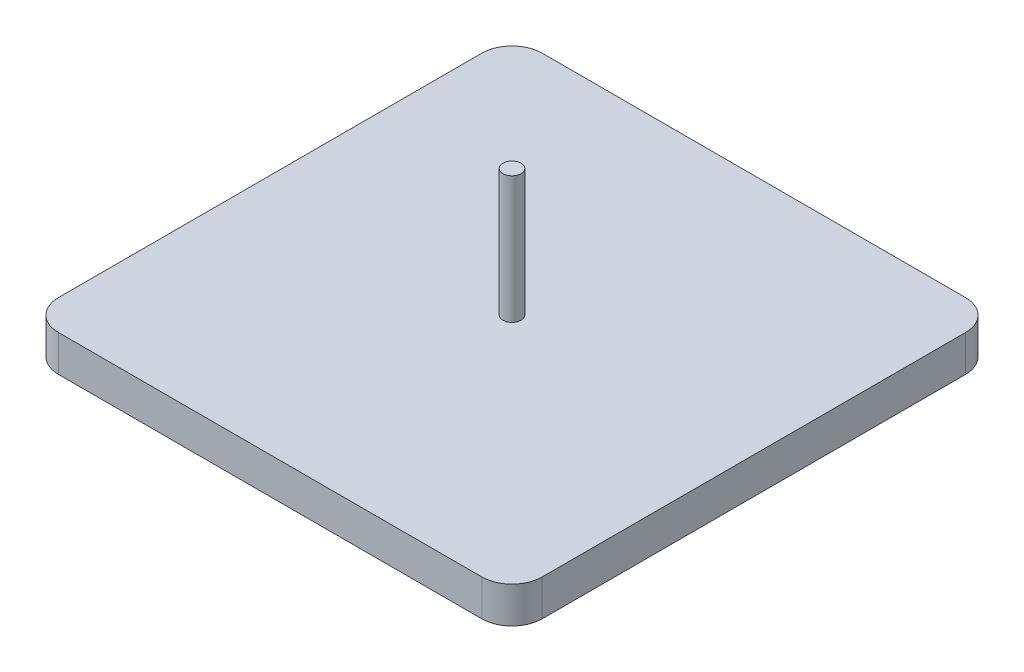
SolidWorks part; units mm, degrees
ref_plane "Front Plane" through (0, 0, 0) normal (0, 0, 1) x (1, 0, 0)
ref_plane "Top Plane" through (0, 0, 0) normal (0, 1, 0) x (1, 0, 0)
ref_plane "Right Plane" through (0, 0, 0) normal (1, 0, 0) x (0, 0, -1)
sketch "Sketch1" plane through (0, 0, 0) normal (0, 1, 0) x (1, 0, 0)
  line L1 (-21.4242, 53.9849) -> (58.5758, 53.9849)
  line L2 (-21.4242, 53.9849) -> (-21.4242, -26.0151)
  line L3 (-21.4242, -26.0151) -> (58.5758, -26.0151)
  line L4 (58.5758, 53.9849) -> (58.5758, -26.0151)
extrude "Boss-Extrude1" add sketch "Sketch1" along normal blind 6
fillet "Fillet1" radius 5 4 edges at (-21.4242, 3, -53.9849) (58.5758, 3, -53.9849) (-21.4242, 3, 26.0151) (58.5758, 3, 26.0151)
sketch "Sketch2" plane through (0, 6, 0) normal (0, 1, 0) x (1, 0, 0)
  line L0 (18.5758, 53.9849) -> (18.5758, -26.0151)
  line L1 (53.5758, 53.9849) -> (-16.4242, 53.9849) construction
  line L2 (-16.4242, -26.0151) -> (53.5758, -26.0151) construction
  point P6 (0, 0)
sketch "Sketch3" plane through (0, 6, 0) normal (0, 1, 0) x (1, 0, 0)
  line L0 (18.5758, 53.9849) -> (18.5758, -26.0151)
  line L1 (18.5758, -26.0151) -> (58.5758, 13.9849)
  line L2 (58.5758, -21.0151) -> (58.5758, 48.9849) construction
  line L3 (58.5758, 13.9849) -> (-21.4242, 13.9849)
  line L4 (-21.4242, 48.9849) -> (-21.4242, -21.0151) construction
  circle A0 centre (18.5758, 13.9849) radius 1.5
  dimension "D1" = 3
extrude "Boss-Extrude2" add sketch "Sketch3" against normal blind 3 and the other way blind 21 contours L0 A0 L3 | L3 A0 L0 | L0 A0 L3 | L3 A0 L0
